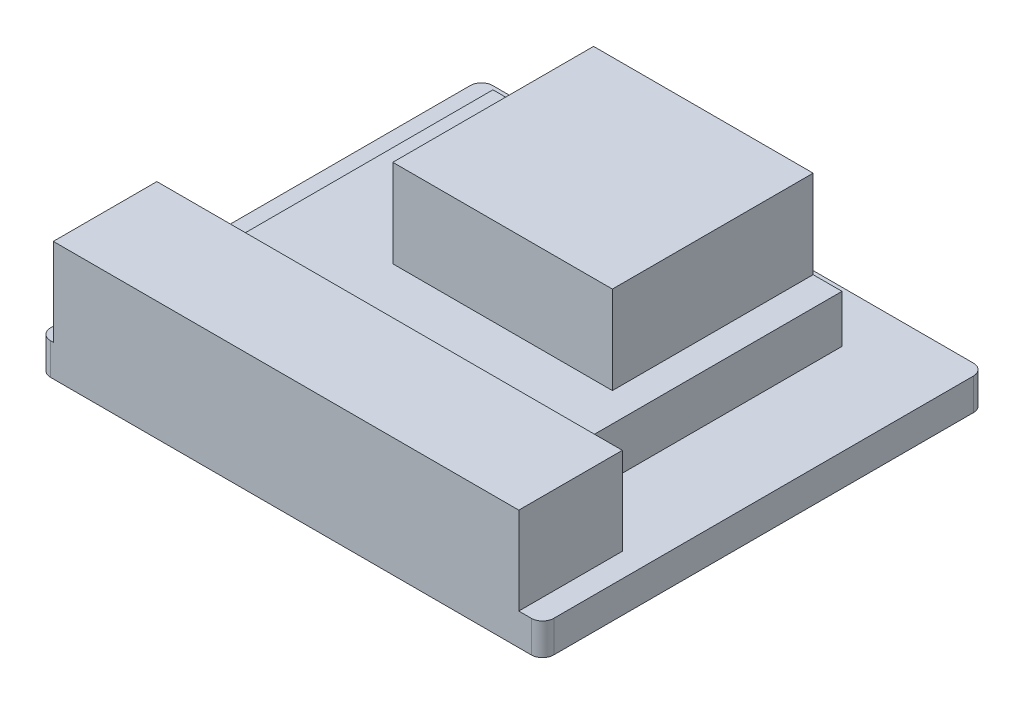
SolidWorks part; units mm, degrees
ref_plane "Front Plane" through (0, 0, 0) normal (0, 0, 1) x (1, 0, 0)
ref_plane "Top Plane" through (0, 0, 0) normal (0, 1, 0) x (1, 0, 0)
ref_plane "Right Plane" through (0, 0, 0) normal (1, 0, 0) x (0, 0, -1)
sketch "Sketch1" plane through (0, 0, 0) normal (0, 1, 0) x (1, 0, 0)
  line L0 (-51.5, -42.95) -> (-51.5, 42.95)
  line L1 (-49.2, 45.25) -> (49.2, 45.25)
  line L2 (51.5, 42.95) -> (51.5, -42.95)
  line L3 (49.2, -45.25) -> (-49.2, -45.25)
  arc A0 (-49.2, -45.25) -> (-51.5, -42.95) centre (-49.2, -42.95) cw
  arc A1 (-51.5, 42.95) -> (-49.2, 45.25) centre (-49.2, 42.95) cw
  arc A2 (49.2, 45.25) -> (51.5, 42.95) centre (49.2, 42.95) cw
  arc A3 (49.2, -45.25) -> (51.5, -42.95) centre (49.2, -42.95) ccw
extrude "Boss-Extrude1" add sketch "Sketch1" along normal blind 6.5
sketch "Sketch2" plane through (0, 6.5, 0) normal (0, 1, 0) x (1, 0, 0)
  line L0 (-51.5, 42.95) -> (-51.5, -42.95) construction
  line L1 (-48.65, -45.25) -> (46.64, -45.25)
  line L2 (-48.65, -45.25) -> (-48.65, -24.05)
  line L3 (-48.65, -24.05) -> (46.64, -24.05)
  line L4 (46.64, -45.25) -> (46.64, -24.05)
  line L5 (-49.2, -45.25) -> (49.2, -45.25) construction
  line L6 (51.5, -42.95) -> (51.5, 42.95) construction
  dimension "D1" = 2.85
  dimension "D2" = 0
  dimension "D3" = 4.86
  dimension "D4" = 21.2
extrude "Boss-Extrude2" add sketch "Sketch2" along normal blind 17.9
sketch "Sketch3" plane through (0, 6.5, 0) normal (0, 1, 0) x (1, 0, 0)
  line L0 (49.2, 45.25) -> (-49.2, 45.25) construction
  line L1 (-38.65, 34.75) -> (32.8, 34.75)
  line L2 (-38.65, 34.75) -> (-38.65, -16.25)
  line L3 (-38.65, -16.25) -> (32.8, -16.25)
  line L4 (32.8, 34.75) -> (32.8, -16.25)
  line L5 (51.5, -42.95) -> (51.5, 42.95) construction
  line L6 (-51.5, 42.95) -> (-51.5, -42.95) construction
  dimension "D1" = 10.5
  dimension "D2" = 51
  dimension "D3" = 18.7
  dimension "D4" = 12.85
extrude "Boss-Extrude3" add sketch "Sketch3" along normal blind 9.77
sketch "Sketch4" plane through (0, 16.27, 0) normal (0, 1, 0) x (1, 0, 0)
  line L0 (32.8, -16.25) -> (32.8, 34.75) construction
  line L1 (-18.05, 34.75) -> (26.9, 34.75)
  line L2 (-18.05, 34.75) -> (-18.05, -6.35)
  line L3 (-18.05, -6.35) -> (26.9, -6.35)
  line L4 (26.9, 34.75) -> (26.9, -6.35)
  line L5 (-38.65, 34.75) -> (-38.65, -16.25) construction
  line L6 (32.8, 34.75) -> (-38.65, 34.75) construction
  line L7 (-38.65, -16.25) -> (32.8, -16.25) construction
  dimension "D1" = 5.9
  dimension "D2" = 20.6
  dimension "D3" = 0
  dimension "D4" = 9.9
extrude "Boss-Extrude4" add sketch "Sketch4" along normal blind 18
